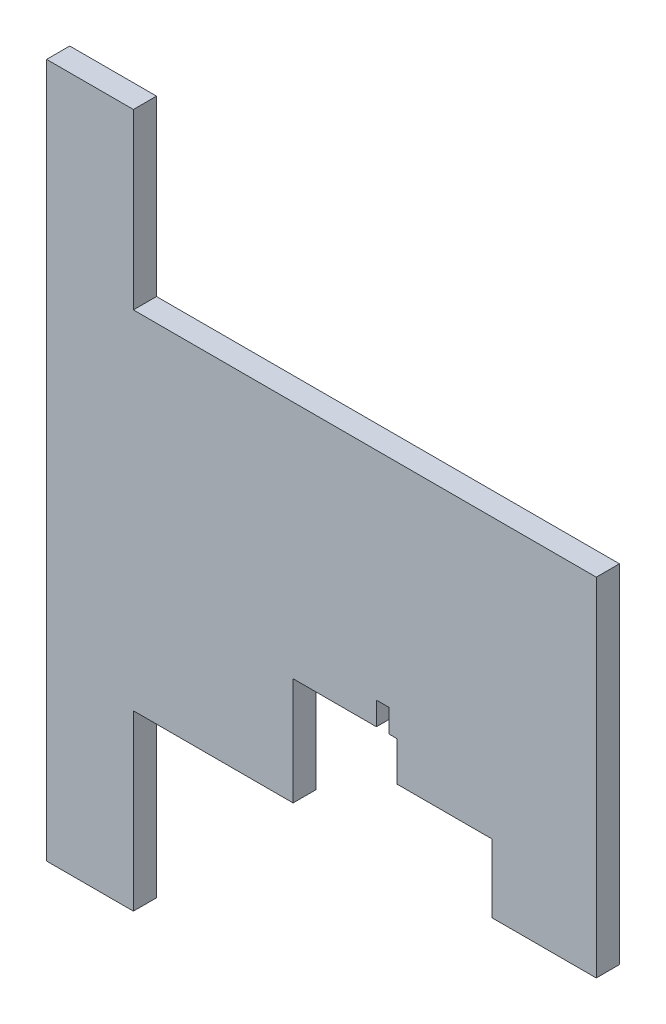
SolidWorks part; units mm, degrees
material "Beech"
ref_plane "Front Plane" through (0, 0, 0) normal (0, 0, 1) x (1, 0, 0)
ref_plane "Top Plane" through (0, 0, 0) normal (0, 1, 0) x (1, 0, 0)
ref_plane "Right Plane" through (0, 0, 0) normal (1, 0, 0) x (0, 0, -1)
sketch "Sketch1" plane through (0, 0, 0) normal (0, 0, 1) x (1, 0, 0)
  line L0 (0, 0) -> (101.6, 0)
  line L1 (101.6, 0) -> (101.6, -76.2)
  line L2 (101.6, -76.2) -> (0, -76.2)
  line L3 (0, 0) -> (0, 38.1)
  line L4 (0, 38.1) -> (-19.05, 38.1)
  line L5 (-19.05, 38.1) -> (-19.05, -114.3)
  line L6 (-19.05, -114.3) -> (0, -114.3)
  line L7 (0, -114.3) -> (0, -76.2)
  dimension "D1" = 101.6
  dimension "D2" = 76.2
  dimension "D3" = 152.4
  dimension "D4" = 38.1
  dimension "D5" = 19.05
extrude "Boss-Extrude1" add sketch "Sketch1" along normal blind 5.08
sketch "Sketch2" plane through (0, 0, 5.08) normal (0, 0, 1) x (1, 0, 0)
  line L0 (35.052, -76.2) -> (35.052, -52.578)
  line L1 (0, -76.2) -> (101.6, -76.2) construction
  line L2 (35.052, -52.578) -> (53.34, -52.578)
  line L3 (53.34, -52.578) -> (53.34, -47.498)
  line L4 (53.34, -47.498) -> (56.134, -47.498)
  line L5 (56.134, -47.498) -> (56.134, -52.578)
  line L6 (56.134, -52.578) -> (57.912, -52.578)
  line L8 (78.74, -61.214) -> (78.74, -76.2)
  line L9 (35.052, -76.2) -> (78.74, -76.2)
  line L10 (101.6, -76.2) -> (101.6, 0) construction
  line L11 (57.912, -52.578) -> (57.912, -61.214)
  line L12 (57.912, -61.214) -> (78.74, -61.214)
  dimension "D1" = 43.688
  dimension "D2" = 20.828
  dimension "D3" = 2.794
  dimension "D4" = 5.08
  dimension "D5" = 18.288
  dimension "D6" = 14.986
  dimension "D7" = 1.778
  dimension "D8" = 8.636
extrude "Cut-Extrude1" cut sketch "Sketch2" against normal through all both and the other way through all contours L2 L3 L4 L5 L6 L11 L12 L8 L9 L0
